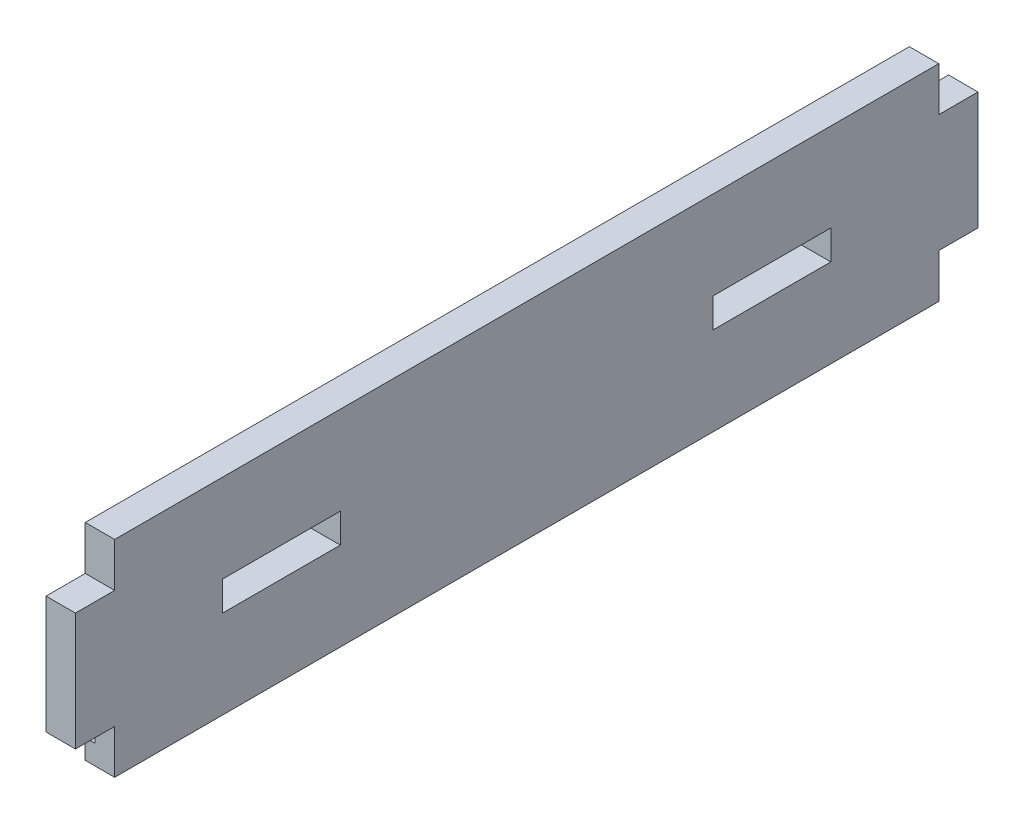
SolidWorks part; units mm, degrees
ref_plane "Front Plane" through (0, 0, 0) normal (0, 0, 1) x (1, 0, 0)
ref_plane "Top Plane" through (0, 0, 0) normal (0, 1, 0) x (1, 0, 0)
ref_plane "Right Plane" through (0, 0, 0) normal (1, 0, 0) x (0, 0, -1)
sketch "Sketch1" plane through (0, 0, 0) normal (0, 0, 1) x (1, 0, 0)
  line L1 (49060.4061, 709.3894) -> (49079.4561, 709.3894)
  line L2 (49060.4061, 709.3894) -> (49060.4061, 576.0394)
  line L3 (49060.4061, 576.0394) -> (49079.4561, 576.0394)
  line L4 (49079.4561, 709.3894) -> (49079.4561, 576.0394)
  dimension "D1" = 19.05
  dimension "D2" = 133.35
extrude "Boss-Extrude1" add sketch "Sketch1" along normal blind 584.2
sketch "Sketch2" plane through (49060.4061, 0, 0) normal (-1, 0, 0) x (0, 0, 1)
  line L0 (292.1, 709.3894) -> (292.1, 576.0394) construction
  line L1 (584.2, 709.3894) -> (0, 709.3894) construction
  line L2 (584.2, 576.0394) -> (0, 576.0394) construction
  line L3 (0, 709.3894) -> (0, 576.0394) construction
  line L4 (95.25, 652.2394) -> (171.45, 652.2394)
  line L5 (95.25, 652.2394) -> (95.25, 633.1894)
  line L6 (95.25, 633.1894) -> (171.45, 633.1894)
  line L7 (171.45, 652.2394) -> (171.45, 633.1894)
  line L8 (133.35, 709.3894) -> (133.35, 652.2394) construction
  line L9 (133.35, 652.2394) -> (133.35, 633.1894) construction
  line L10 (133.35, 633.1894) -> (133.35, 576.0394) construction
  line L11 (488.95, 652.2394) -> (488.95, 633.1894)
  line L12 (488.95, 652.2394) -> (412.75, 652.2394)
  line L13 (412.75, 652.2394) -> (412.75, 633.1894)
  line L14 (488.95, 633.1894) -> (412.75, 633.1894)
  line L15 (95.25, 642.7144) -> (75.7808, 642.7144) construction
  line L16 (584.2, 709.3894) -> (584.2, 680.8144)
  line L17 (0, 709.3894) -> (25.4, 709.3894)
  line L18 (0, 709.3894) -> (0, 680.8144)
  line L20 (0, 680.8144) -> (25.4, 680.8144)
  line L21 (25.4, 709.3894) -> (25.4, 680.8144)
  line L22 (584.2, 709.3894) -> (558.8, 709.3894)
  line L23 (558.8, 709.3894) -> (558.8, 680.8144)
  line L24 (584.2, 680.8144) -> (558.8, 680.8144)
  line L25 (0, 576.0394) -> (0, 604.6144)
  line L26 (0, 576.0394) -> (25.4, 576.0394)
  line L27 (25.4, 576.0394) -> (25.4, 604.6144)
  line L28 (0, 604.6144) -> (25.4, 604.6144)
  line L29 (584.2, 576.0394) -> (584.2, 604.6144)
  line L30 (584.2, 576.0394) -> (558.8, 576.0394)
  line L31 (558.8, 576.0394) -> (558.8, 604.6144)
  line L32 (584.2, 604.6144) -> (558.8, 604.6144)
  dimension "D1" = 19.05
  dimension "D2" = 76.2
  dimension "D3" = 95.25
  dimension "D4" = 25.4
  dimension "D5" = 28.575
extrude "Cut-Extrude1" cut sketch "Sketch2" against normal through all
sketch "Sketch3" plane through (0, 0, 584.2) normal (0, 0, 1) x (1, 0, 0)
  line L0 (49060.4061, 680.8144) -> (49060.4061, 604.6144) construction
  line L1 (49060.4061, 595.0894) -> (49066.7561, 595.0894)
  line L2 (49060.4061, 595.0894) -> (49060.4061, 588.7394)
  line L3 (49060.4061, 588.7394) -> (49066.7561, 588.7394)
  line L4 (49066.7561, 595.0894) -> (49066.7561, 588.7394)
  line L5 (49060.4061, 576.0394) -> (49079.4561, 576.0394) construction
  dimension "D1" = 6.35
  dimension "D2" = 6.35
  dimension "D3" = 12.7
extrude "Cut-Extrude2" cut sketch "Sketch3" against normal through all
